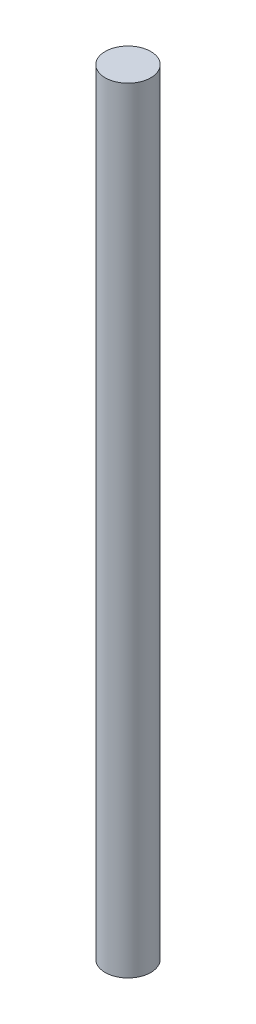
SolidWorks part; units mm, degrees
ref_plane "Front Plane" through (0, 0, 0) normal (0, 0, 1) x (1, 0, 0)
ref_plane "Top Plane" through (0, 0, 0) normal (0, 1, 0) x (1, 0, 0)
ref_plane "Right Plane" through (0, 0, 0) normal (1, 0, 0) x (0, 0, -1)
sketch "Sketch1" plane through (0, 0, 0) normal (0, 1, 0) x (1, 0, 0)
  circle A0 centre (-105.4031, -22.8645) radius 10
  dimension "D1" = 20
extrude "Boss-Extrude1" add sketch "Sketch1" along normal blind 340
